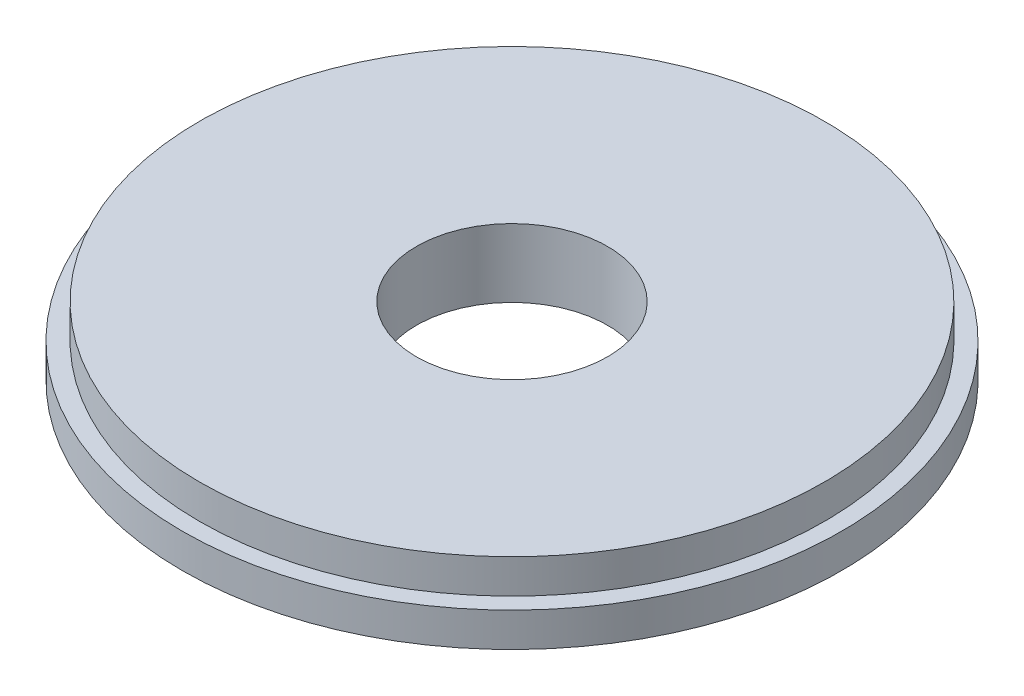
SolidWorks part; units mm, degrees
ref_plane "Front Plane" through (0, 0, 0) normal (0, 0, 1) x (1, 0, 0)
ref_plane "Top Plane" through (0, 0, 0) normal (0, 1, 0) x (1, 0, 0)
ref_plane "Right Plane" through (0, 0, 0) normal (1, 0, 0) x (0, 0, -1)
sketch "Sketch1" plane through (0, 0, 0) normal (0, 1, 0) x (1, 0, 0)
  circle A0 centre (0, 0) radius 48.25
  dimension "D1" = 96.5
extrude "Boss-Extrude1" add sketch "Sketch1" along normal blind 5
sketch "Sketch2" plane through (0, 5, 0) normal (0, 1, 0) x (1, 0, 0)
  circle A0 centre (0, 0) radius 45.75
  dimension "D1" = 91.5
extrude "Boss-Extrude2" add sketch "Sketch2" along normal blind 5
sketch "Sketch3" plane through (0, 10, 0) normal (0, 1, 0) x (1, 0, 0)
  circle A0 centre (0, 0) radius 14
  dimension "D1" = 28
extrude "Cut-Extrude1" cut sketch "Sketch3" against normal through all
